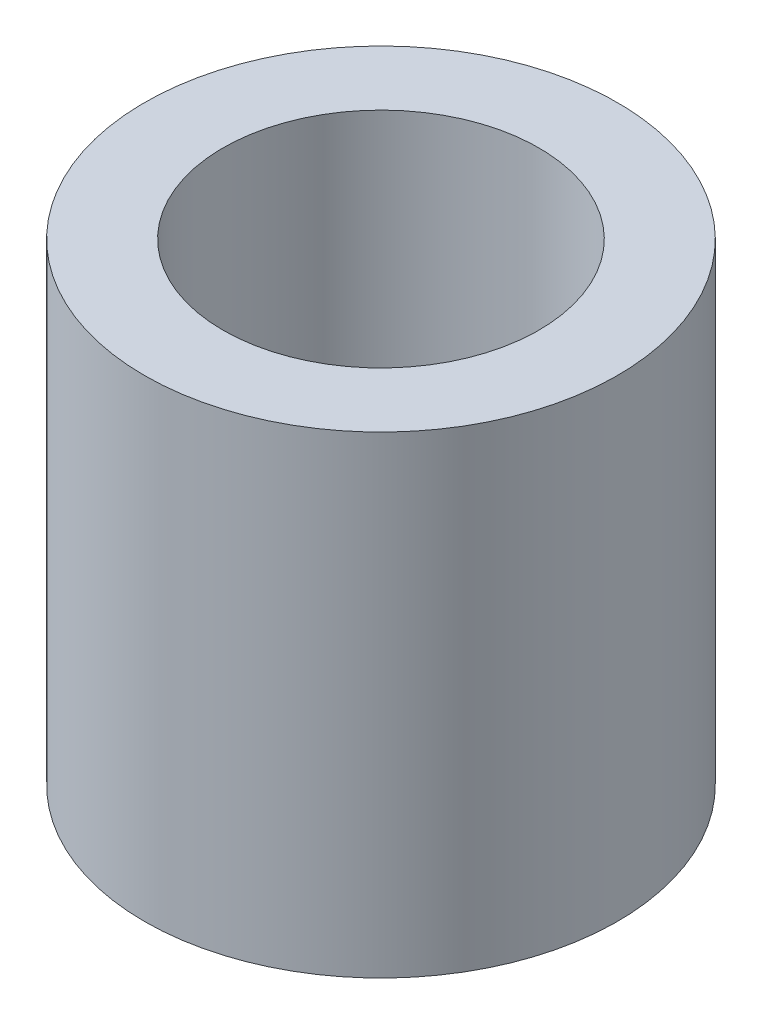
SolidWorks part; units mm, degrees
ref_plane "Front Plane" through (0, 0, 0) normal (0, 0, 1) x (1, 0, 0)
ref_plane "Top Plane" through (0, 0, 0) normal (0, 1, 0) x (1, 0, 0)
ref_plane "Right Plane" through (0, 0, 0) normal (1, 0, 0) x (0, 0, -1)
sketch "Sketch1" plane through (0, 0, 0) normal (0, 1, 0) x (1, 0, 0)
  circle A0 centre (0, 0) radius 25.4
  circle A1 centre (0, 0) radius 16.9684
extrude "Boss-Extrude1" add sketch "Sketch1" along normal blind 50.8
